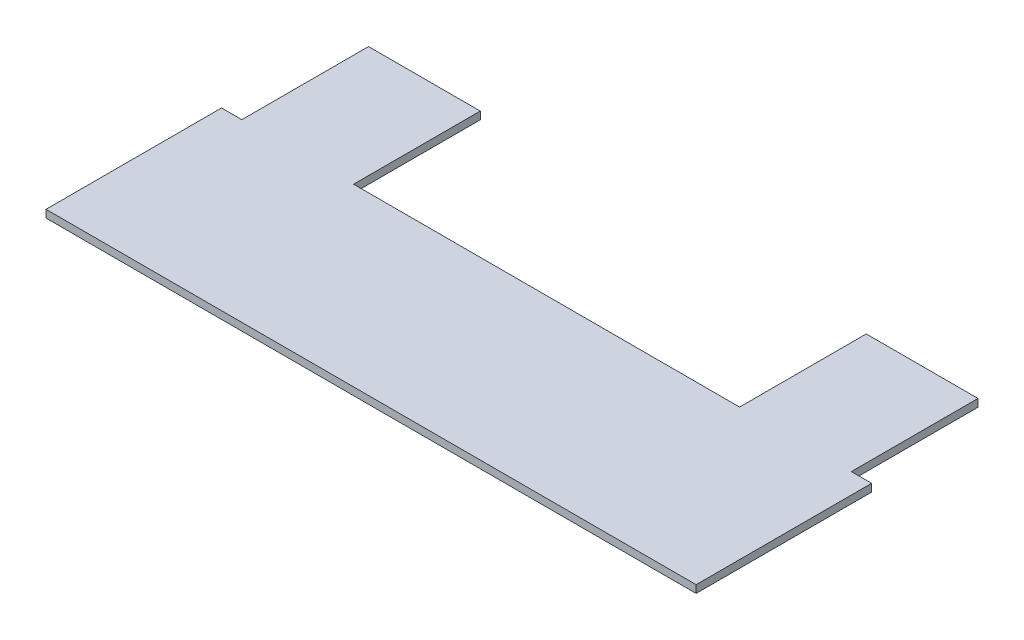
SolidWorks part; units mm, degrees
material "6061-T6 (SS)"
ref_plane "Front Plane" through (0, 0, 0) normal (0, 0, 1) x (1, 0, 0)
ref_plane "Top Plane" through (0, 0, 0) normal (0, 1, 0) x (1, 0, 0)
ref_plane "Right Plane" through (0, 0, 0) normal (1, 0, 0) x (0, 0, -1)
sketch "Sketch1" plane through (0, 0, 0) normal (0, 1, 0) x (1, 0, 0)
  line L1 (-203.2, -94.4562) -> (203.2, -94.4562)
  line L2 (-203.2, -94.4562) -> (-203.2, 94.4562)
  line L3 (-203.2, 94.4562) -> (203.2, 94.4562)
  line L4 (203.2, -94.4562) -> (203.2, 94.4562)
  line L5 (-203.2, -94.4562) -> (203.2, 94.4562) construction
  line L6 (-203.2, 94.4562) -> (203.2, -94.4562) construction
  point P0 (0, 0)
  dimension "D1" = 406.4
  dimension "D2" = 188.9125
extrude "Boss-Extrude1" add sketch "Sketch1" along normal blind 4.7625
sketch "Sketch2" plane through (0, 4.7625, 0) normal (0, 1, 0) x (1, 0, 0)
  line L0 (203.2, 94.4562) -> (-203.2, 94.4562) construction
  line L1 (-203.2, 94.4562) -> (-190.5, 94.4562)
  line L2 (-203.2, 94.4562) -> (-203.2, 15.2743)
  line L3 (-203.2, 15.2743) -> (-190.5, 15.2743)
  line L4 (-190.5, 94.4562) -> (-190.5, 15.2743)
  line L5 (203.2, 94.4562) -> (190.5, 94.4562)
  line L6 (203.2, 94.4562) -> (203.2, 15.2743)
  line L7 (203.2, 15.2743) -> (190.5, 15.2743)
  line L8 (190.5, 94.4562) -> (190.5, 15.2743)
  line L9 (-120.65, 15.2743) -> (120.65, 15.2743)
  line L10 (-120.65, 15.2743) -> (-120.65, 94.4562)
  line L11 (-120.65, 94.4562) -> (120.65, 94.4562)
  line L12 (120.65, 15.2743) -> (120.65, 94.4562)
  line L13 (-120.65, 15.2743) -> (120.65, 94.4562) construction
  line L14 (-120.65, 94.4562) -> (120.65, 15.2743) construction
  point P10 (0, 54.8653)
  dimension "D1" = 79.182
  dimension "D2" = 79.182
  dimension "D3" = 12.7
  dimension "D4" = 12.7
  dimension "D5" = 79.182
  dimension "D6" = 241.3
extrude "Cut-Extrude1" cut sketch "Sketch2" against normal up to surface (4.7625 mm away) up to face at (0, 0, 0)
equation "\"D2@Sketch2\"=\"D1@Sketch2\""
equation "\"D4@Sketch2\"=\"D3@Sketch2\""
equation "\"D5@Sketch2\"=\"D1@Sketch2\""
